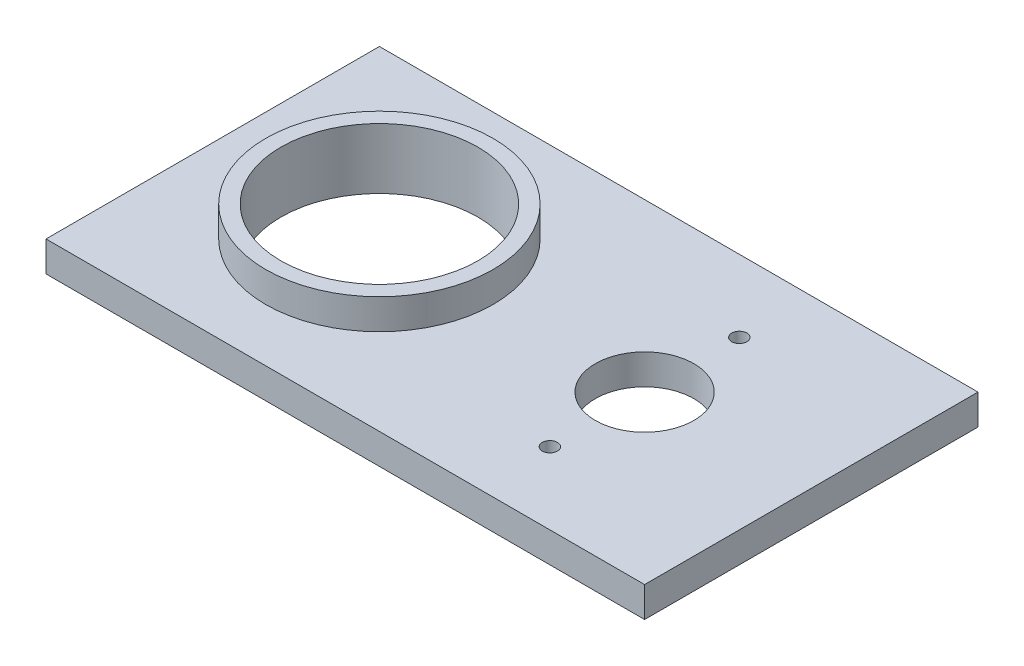
SolidWorks part; units mm, degrees
material "Custom Plastic"
ref_plane "Ön Düzlem" through (0, 0, 0) normal (0, 0, 1) x (1, 0, 0)
ref_plane "Üst Düzlem" through (0, 0, 0) normal (0, 1, 0) x (1, 0, 0)
ref_plane "Sağ Düzlem" through (0, 0, 0) normal (1, 0, 0) x (0, 0, -1)
sketch "Çizim2" plane through (0, 0, 0) normal (0, 1, 0) x (1, 0, 0)
  line L9 (-57, -22) -> (22, -22)
  line L10 (-57, -22) -> (-57, 22)
  line L11 (-57, 22) -> (22, 22)
  line L12 (22, -22) -> (22, 22)
  circle A0 centre (0, 0) radius 6.5
  circle A2 centre (0, 12.5) radius 1
  circle A3 centre (0, -12.5) radius 1
  circle A5 centre (-35, 0) radius 13
  dimension "D1" = 13
  dimension "D3" = 2
  dimension "D4" = 2
  dimension "D7" = 26
  dimension "D6" = 35
extrude "Yükseklik-Ekstrüzyon1" add sketch "Çizim2" along normal blind 4
sketch "Çizim3" plane through (0, 4, 0) normal (0, 1, 0) x (1, 0, 0)
  circle A0 centre (-35, 0) radius 15
  circle A1 centre (-35, 0) radius 13
  dimension "D1" = 30
extrude "Yükseklik-Ekstrüzyon2" add sketch "Çizim3" along normal blind 4
